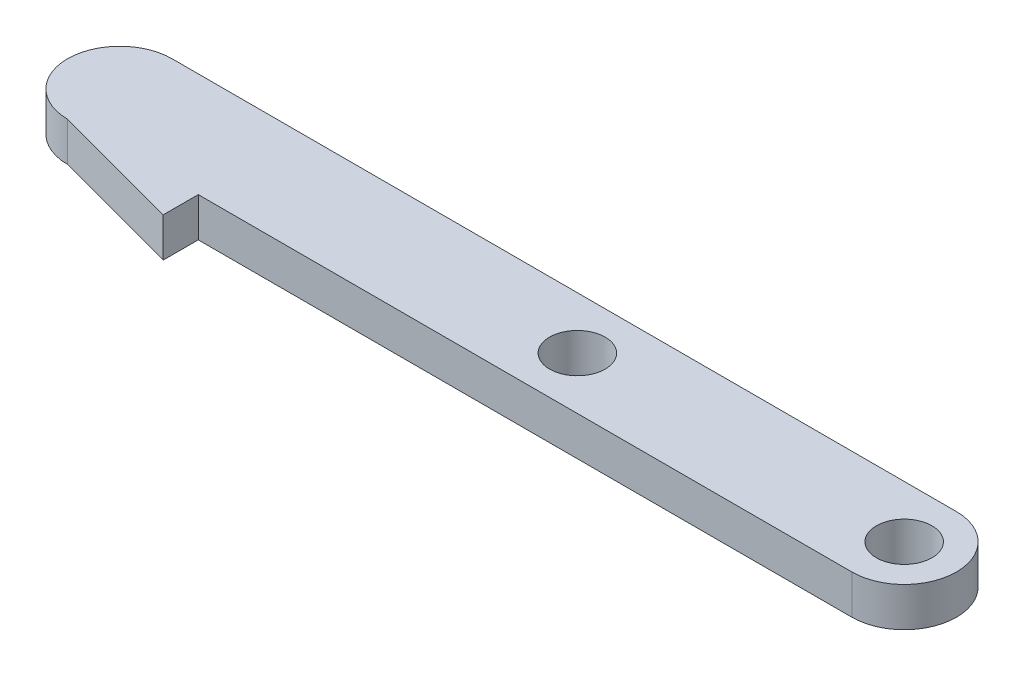
SolidWorks part; units mm, degrees
material "ABS"
ref_plane "Front Plane" through (0, 0, 0) normal (0, 0, 1) x (1, 0, 0)
ref_plane "Top Plane" through (0, 0, 0) normal (0, 1, 0) x (1, 0, 0)
ref_plane "Right Plane" through (0, 0, 0) normal (1, 0, 0) x (0, 0, -1)
sketch "Sketch1" plane through (0, 0, 0) normal (0, 1, 0) x (1, 0, 0)
  line L0 (-30, 0) -> (30, 0) construction
  line L1 (-30, 4) -> (30, 4)
  line L2 (-30, -4) -> (30, -4)
  arc A0 (-30, 4) -> (-30, -4) centre (-30, 0) ccw
  arc A1 (30, -4) -> (30, 4) centre (30, 0) ccw
  circle A2 centre (30, 0) radius 2.125
  circle A3 centre (5, 0) radius 2.125
  point P2 (0, 0)
  dimension "D3" = 4.25
  dimension "D4" = 4.25
  dimension "D1" = 8
  dimension "D2" = 60
  dimension "D5" = 25
extrude "Boss-Extrude1" add sketch "Sketch1" along normal blind 3
sketch "Sketch3" plane through (0, 0, 0) normal (0, -1, 0) x (1, 0, 0)
  line L0 (-30, 4) -> (-20, 6.6795)
  line L1 (-20, 6.6795) -> (-20, 4)
  line L2 (-30, 4) -> (30, 4) construction
  line L3 (-20, 4) -> (-30, 4)
  dimension "D1" = 15
  dimension "D2" = 10
extrude "Boss-Extrude2" add sketch "Sketch3" against normal blind 3
